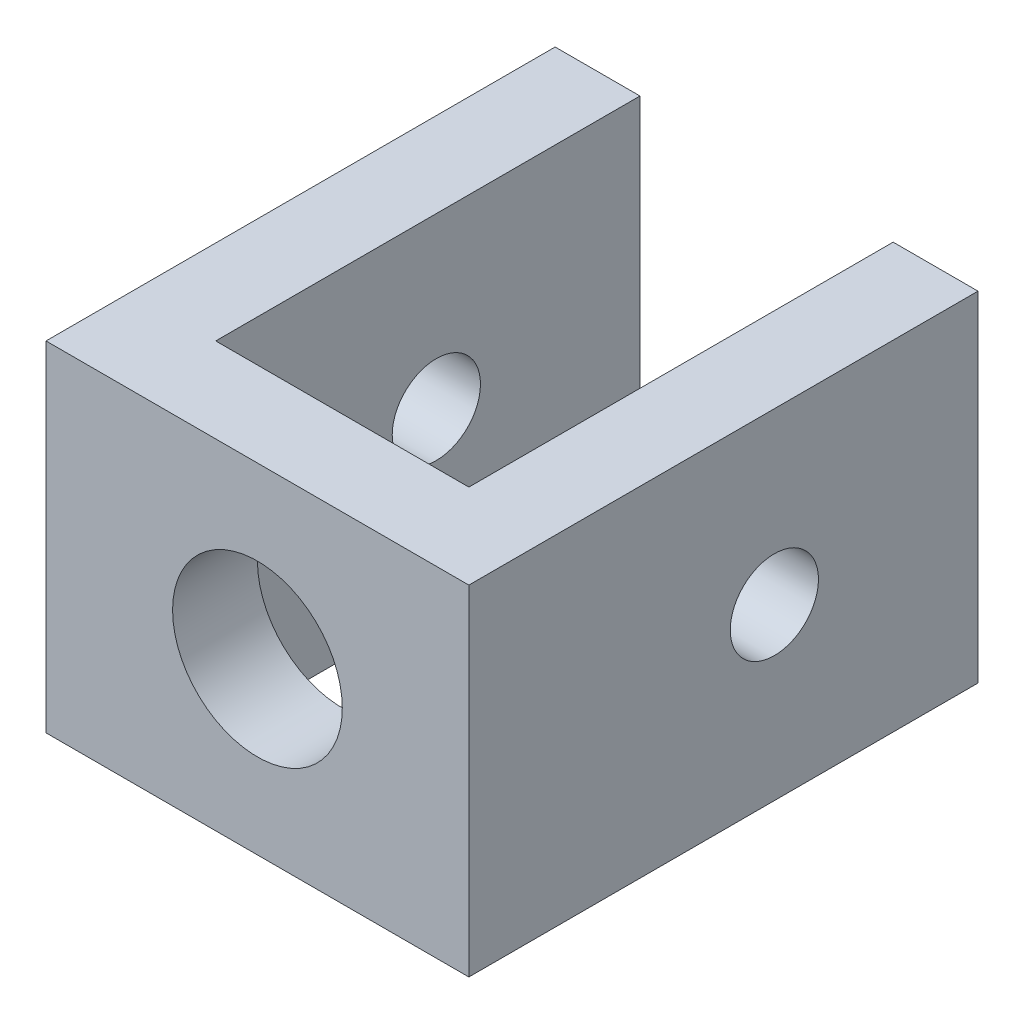
SolidWorks part; units mm, degrees
ref_plane "Front Plane" through (0, 0, 0) normal (0, 0, 1) x (1, 0, 0)
ref_plane "Top Plane" through (0, 0, 0) normal (0, 1, 0) x (1, 0, 0)
ref_plane "Right Plane" through (0, 0, 0) normal (1, 0, 0) x (0, 0, -1)
sketch "Sketch1" plane through (0, 0, 0) normal (0, 1, 0) x (1, 0, 0)
  line L0 (0, 0) -> (0, 38.1)
  line L1 (0, 38.1) -> (6.35, 38.1)
  line L2 (6.35, 38.1) -> (6.35, 6.35)
  line L3 (6.35, 6.35) -> (25.2944, 6.35)
  line L7 (31.6444, 0) -> (0, 0)
  line L8 (15.8222, 0) -> (15.8222, 6.35) construction
  line L9 (31.6444, 38.1) -> (25.2944, 38.1)
  line L10 (25.2944, 38.1) -> (25.2944, 6.35)
  line L11 (31.6444, 0) -> (31.6444, 38.1)
  dimension "D1" = 6.35
  dimension "D2" = 6.35
  dimension "D3" = 38.1
extrude "Boss-Extrude1" add sketch "Sketch1" along normal blind 25.4
sketch "Sketch2" plane through (0, 0, 0) normal (0, 0, 1) x (1, 0, 0)
  line L0 (15.8222, 25.4) -> (15.8222, 0) construction
  line L1 (0, 25.4) -> (31.6444, 25.4) construction
  line L2 (0, 0) -> (31.6444, 0) construction
  line L3 (0, 12.7) -> (31.6444, 12.7) construction
  line L4 (0, 25.4) -> (0, 0) construction
  line L5 (31.6444, 25.4) -> (31.6444, 0) construction
  circle A0 centre (15.8222, 12.7) radius 6.35
extrude "Cut-Extrude1" cut sketch "Sketch2" against normal through all
sketch "Sketch5" plane through (6.35, 0, 0) normal (1, 0, 0) x (0, 0, -1)
  line L0 (6.35, 12.7) -> (38.1, 12.7) construction
  line L1 (6.35, 25.4) -> (6.35, 0) construction
  line L2 (38.1, 25.4) -> (38.1, 0) construction
  line L3 (38.1, 25.4) -> (38.1, 0) construction
  circle A0 centre (22.86, 12.7) radius 3.302
  point P14 (0, 0)
  dimension "D1" = 15.24
extrude "Cut-Extrude2" cut sketch "Sketch5" against normal through all and the other way through all
